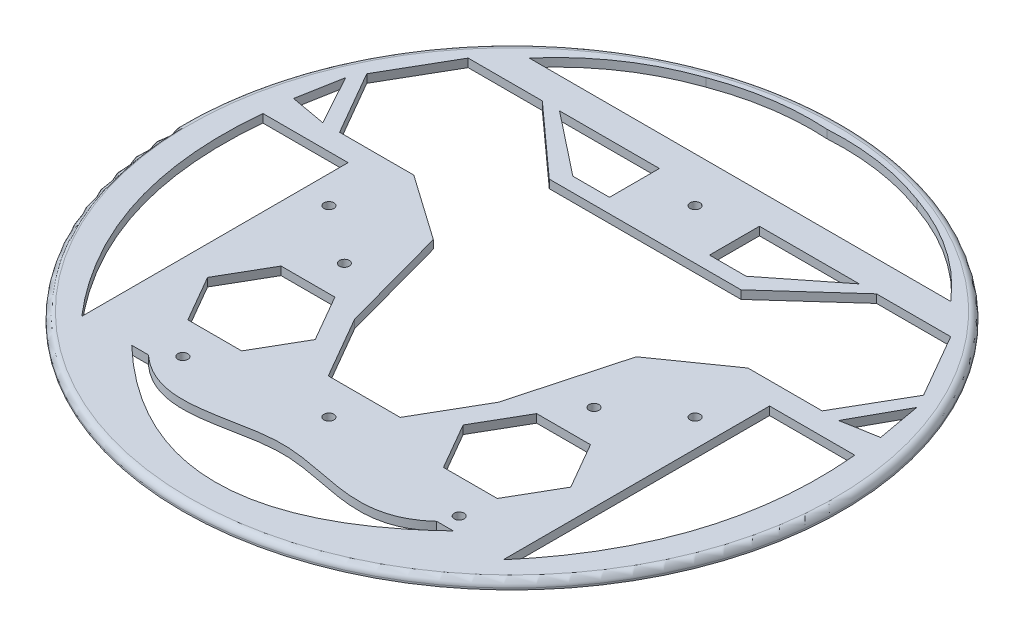
SolidWorks part; units mm, degrees
ref_plane "Front Plane" through (0, 0, 0) normal (0, 0, 1) x (1, 0, 0)
ref_plane "Top Plane" through (0, 0, 0) normal (0, 1, 0) x (1, 0, 0)
ref_plane "Right Plane" through (0, 0, 0) normal (1, 0, 0) x (0, 0, -1)
sketch "Sketch1" plane through (0, 0, 0) normal (0, 1, 0) x (1, 0, 0)
  circle A0 centre (0, 0) radius 99
extrude "Boss-Extrude1" add sketch "Sketch1" against normal blind 2.5 and the other way blind 4
sketch "Sketch3" plane through (0, 4, 0) normal (0, 1, 0) x (1, 0, 0)
  circle A0 centre (-55, 0) radius 1.5
  circle A1 centre (55, 0) radius 1.5
  circle A2 centre (0, -55) radius 1.5
extrude "Cut-Extrude2" cut sketch "Sketch3" against normal blind 20.5
sketch "Sketch4" plane through (0, 4, 0) normal (0, 1, 0) x (1, 0, 0)
  circle A0 centre (-37.676, -12.6871) radius 1.5
  circle A1 centre (-37.676, -61.1871) radius 1.5
  circle A2 centre (45.324, -61.1871) radius 1.5
  circle A3 centre (37.324, -12.6871) radius 1.5
extrude "Cut-Extrude3" cut sketch "Sketch4" against normal blind 20.5
sketch "Sketch5" plane through (0, 4, 0) normal (0, 1, 0) x (1, 0, 0)
  line L0 (0, 0) -> (0, 40)
  line L1 (28.8003, 40) -> (39.0457, 40)
  line L2 (28.8003, 40) -> (14.4001, 64.9418)
  line L3 (14.4001, 64.9418) -> (-14.4001, 64.9418)
  line L4 (-14.4001, 64.9418) -> (-28.8003, 40)
  line L5 (-28.8003, 40) -> (-14.4001, 15.0582)
  line L6 (-14.4001, 15.0582) -> (14.4001, 15.0582)
  line L7 (14.4001, 15.0582) -> (28.8003, 40)
  line L8 (21.6002, -25.6723) -> (10.8001, -6.966)
  line L9 (10.8001, -6.966) -> (-10.8001, -6.966)
  line L10 (-10.8001, -6.966) -> (-21.6002, -25.6723)
  line L11 (-21.6002, -25.6723) -> (-10.8001, -44.3786)
  line L12 (-10.8001, -44.3786) -> (10.8001, -44.3786)
  line L13 (10.8001, -44.3786) -> (21.6002, -25.6723)
  line L14 (83.6324, 40) -> (72.4857, 59.3066)
  line L15 (72.4857, 59.3066) -> (50.1924, 59.3066)
  line L16 (50.1924, 59.3066) -> (39.0457, 40)
  line L17 (39.0457, 40) -> (50.1924, 20.6934)
  line L18 (50.1924, 20.6934) -> (72.4857, 20.6934)
  line L19 (72.4857, 20.6934) -> (83.6324, 40)
  line L20 (-28.8003, 40) -> (-39.0503, 40)
  line L21 (0, 40) -> (-61.34, 40)
  line L24 (-39.0503, 40) -> (-50.1951, 59.3035)
  line L25 (-50.1951, 59.3035) -> (-72.4849, 59.3035)
  line L26 (-72.4849, 59.3035) -> (-83.6297, 40)
  line L27 (-83.6297, 40) -> (-72.4849, 20.6965)
  line L28 (-72.4849, 20.6965) -> (-50.1951, 20.6965)
  line L29 (-50.1951, 20.6965) -> (-39.0503, 40)
  circle A0 centre (0, 40) radius 24.9418 construction
  circle A1 centre (0, -25.6723) radius 18.7063 construction
  circle A2 centre (61.3391, 40) radius 19.3066 construction
  circle A3 centre (-61.34, 40) radius 19.3035 construction
extrude "Cut-Extrude4" cut sketch "Sketch5" against normal blind 10
sketch "Sketch6" plane through (0, 4, 0) normal (0, 1, 0) x (1, 0, 0)
  line L1 (-63.3094, 68.4789) -> (63.3094, 68.4789)
  line L2 (0, 68.4789) -> (0, 89.9578)
  line L3 (31.6547, 89.9578) -> (-31.6547, 89.9578)
  line L4 (0, 94.6904) -> (0, 89.9578)
  spline S0 degree 2 poles (-31.6547, 89.9578) (-50.3881, 83.4788) (-63.3094, 68.4789) knots 0 0 0 1 1 1
  spline S1 degree 2 poles (-31.6547, 89.9578) (-16.2344, 95.6989) (0, 94.6904) knots 0 0 0 1 1 1
  spline S2 degree 2 poles (31.6547, 89.9578) (16.2344, 95.6989) (0, 94.6904) knots 0 0 0 1 1 1
  spline S3 degree 2 poles (31.6547, 89.9578) (50.3881, 83.4788) (63.3094, 68.4789) knots 0 0 0 1 1 1
extrude "Cut-Extrude5" cut sketch "Sketch6" against normal blind 10 contours L3 S0 L1 L2 | S3 L3 L2 L1 | S1 L3 L4 | L3 S2 L4
sketch "Sketch7" plane through (0, 4, 0) normal (0, 1, 0) x (1, 0, 0)
  line L0 (-63.3094, -65.9369) -> (-63.3094, 14.0631)
  line L1 (-63.3094, -25.9369) -> (-75.4736, -25.9369)
  line L2 (-63.3094, 14.0631) -> (-88.8973, 14.0631)
  line L3 (-75.4736, -25.9369) -> (-85.4736, -25.9369)
  line L4 (0, 84.4217) -> (0, -91.9001)
  line L5 (63.3094, 14.0631) -> (88.8973, 14.0631)
  line L6 (63.3094, -65.9369) -> (63.3094, 14.0631)
  spline S0 degree 2 poles (-88.8973, 14.0631) (-93.2525, -31.1608) (-63.3094, -65.9369) knots 0 0 0 1 1 1
  spline S1 degree 2 poles (88.8973, 14.0631) (93.2525, -31.1608) (63.3094, -65.9369) knots 0 0 0 1 1 1
extrude "Cut-Extrude6" cut sketch "Sketch7" against normal blind 10 contours L2 S0 L3 L1 L0 | L3 S0 L0 L1 | S1 L5 L6
sketch "Sketch8" plane through (0, 4, 0) normal (0, 1, 0) x (1, 0, 0)
  line L1 (-63.3094, -65.9369) -> (-59.7739, -69.4724)
  line L2 (63.3094, -65.9369) -> (59.7739, -69.4724)
  line L4 (-121.0223, -77.0752) -> (-121.0223, -77.3515)
  line L5 (0, 0) -> (0, 55)
  line L6 (-14.4001, 64.9418) -> (14.4001, 64.9418)
  line L7 (14.4001, 64.9418) -> (28.8003, 40)
  line L8 (28.8003, 40) -> (-28.8003, 40)
  line L9 (-28.8003, 40) -> (-14.4001, 64.9418)
extrude "Boss-Extrude4" add sketch "Sketch8" against normal blind 6.5
sketch "Sketch9" plane through (0, 0, -14.0631) normal (0, 0, 1) x (1, 0, 0)
  line L6 (-99, -2.5) -> (-99, 1.5)
  line L7 (-99, 4) -> (-99, -2.5) construction
  line L8 (-99, 1.5) -> (99, 1.5)
  line L9 (99, -2.5) -> (99, 4) construction
  line L10 (99, 1.5) -> (99, -2.5)
  line L11 (99, -2.5) -> (-99, -2.5)
extrude "Cut-Extrude12" cut sketch "Sketch9" along normal blind 147.5 and the other way blind 90
sketch "Sketch15" plane through (0, 4, 0) normal (0, 1, 0) x (1, 0, 0)
  line L0 (0, 0) -> (0, 55)
  circle A0 centre (0, 55) radius 1.5
extrude "Cut-Extrude13" cut sketch "Sketch15" against normal blind 147.5
sketch "Sketch16" plane through (0, 4, 0) normal (0, 1, 0) x (1, 0, 0)
  line L0 (0, 0) -> (0, -0.0726)
  line L7 (0, -6.966) -> (-43.18, -6.966)
  line L8 (10.8001, -6.966) -> (-10.8001, -6.966) construction
  line L9 (-43.18, -6.966) -> (-43.18, 48.914)
  line L10 (0, -6.966) -> (43.18, -6.966)
  line L11 (43.18, -6.966) -> (43.18, 48.914)
  line L12 (43.18, 48.914) -> (-43.18, 48.914)
  line L13 (-50.1951, 59.3035) -> (-50.1951, 20.6965)
  line L14 (-50.1951, 20.6965) -> (-39.0503, 40)
  line L15 (-39.0503, 40) -> (-50.1951, 59.3035)
  line L16 (50.1924, 59.3066) -> (39.0457, 40)
  line L17 (39.0457, 40) -> (50.1924, 20.6934)
  line L18 (50.1924, 20.6934) -> (50.1924, 59.3066)
  line M18 (-50.1951, 59.3035) -> (-39.0503, 40)
  line M19 (-39.0503, 40) -> (-50.1951, 20.6965)
  line M21 (50.1924, 20.6934) -> (39.0457, 40)
  line M22 (39.0457, 40) -> (50.1924, 59.3066)
extrude "Boss-Extrude12" add sketch "Sketch16" against normal blind 2.5 contours L9 M19 M18 | L18 L11 M21 M22 | L11 M21 M22 | L13 L14 L15
sketch "Sketch17" plane through (0, 4, 0) normal (0, 1, 0) x (1, 0, 0)
  line L0 (0, -6.966) -> (-43.18, -6.966)
  line L1 (10.8001, -6.966) -> (-10.8001, -6.966) construction
  line L2 (-43.18, -6.966) -> (-43.18, 48.914)
  line L3 (0, -6.966) -> (43.18, -6.966)
  line L4 (43.18, -6.966) -> (43.18, 48.914)
  line L5 (43.18, 48.914) -> (-43.18, 48.914)
  line L6 (0, -22.8962) -> (0, -50.8962)
  line L7 (-22.2237, -36.8962) -> (-30.3066, -22.8962)
  line L8 (-30.3066, -22.8962) -> (-46.4724, -22.8962)
  line L9 (-46.4724, -22.8962) -> (-54.5553, -36.8962)
  line L10 (-54.5553, -36.8962) -> (-46.4724, -50.8962)
  line L11 (-46.4724, -50.8962) -> (-30.3066, -50.8962)
  line L12 (-30.3066, -50.8962) -> (-22.2237, -36.8962)
  line L13 (30.3066, -50.8962) -> (22.2237, -36.8962)
  line L14 (46.4724, -50.8962) -> (30.3066, -50.8962)
  line L15 (54.5553, -36.8962) -> (46.4724, -50.8962)
  line L16 (46.4724, -22.8962) -> (54.5553, -36.8962)
  line L17 (30.3066, -22.8962) -> (46.4724, -22.8962)
  line L18 (22.2237, -36.8962) -> (30.3066, -22.8962)
  circle A0 centre (-38.3895, -36.8962) radius 14 construction
extrude "Cut-Extrude14" cut sketch "Sketch17" against normal blind 2.5 contours L11 L12 L7 L8 L9 L10 | L18 L13 L14 L15 L16 L17
sketch "Sketch18" plane through (0, 4, 0) normal (0, 1, 0) x (1, 0, 0)
  line L0 (-63.3094, -65.9369) -> (-48.3094, -65.9369)
  line L1 (63.3094, -65.9369) -> (48.3094, -65.9369)
  line L2 (0, -99) -> (0, -89)
  line L3 (-48.3094, -65.9369) -> (-43.3094, -65.9369)
  line L4 (48.3094, -65.9369) -> (43.3094, -65.9369)
  line L5 (0, -89) -> (0, -69)
  line L6 (-28.4523, -81) -> (-23.5507, -72.2837)
  line L7 (28.4523, -81) -> (23.5507, -72.2837)
  circle A0 centre (0, 0) radius 99 construction
  spline S0 degree 2 poles (-48.3094, -65.9369) (0, -112.0631) (48.3094, -65.9369) knots 0 0 0 1 1 1
  spline S1 degree 3 poles (-43.3094, -65.9369) (-29.6148, -78.4073) (0, -59.5927) (29.6148, -78.4073) (43.3094, -65.9369) knots 0 0 0 0 0.5 1 1 1 1
extrude "Cut-Extrude15" cut sketch "Sketch18" against normal blind 2.5 contours S1 L6 S0 L5 | S1 L3 S0 L6 | S1 L5 S0 L7 | S1 L7 S0 L4
sketch "Sketch19" plane through (0, 4, 0) normal (0, 1, 0) x (1, 0, 0)
  line L14 (-10.8001, -6.966) -> (-30.3066, -22.8962)
  line L15 (-30.3066, -22.8962) -> (-14.4001, 15.0582)
  line L16 (-14.4001, 15.0582) -> (14.4001, 15.0582)
  line L17 (14.4001, 15.0582) -> (30.3066, -22.8962)
  line L18 (30.3066, -22.8962) -> (10.8001, -6.966)
  line L19 (10.8001, -6.966) -> (-10.8001, -6.966)
extrude "Boss-Extrude14" add sketch "Sketch19" against normal blind 2.5
sketch "Sketch20" plane through (0, 4, 0) normal (0, 1, 0) x (1, 0, 0)
  line L24 (-28.8003, 40) -> (-10.8001, -6.966)
  line L51 (-10.8001, -6.966) -> (10.8001, -6.966)
  line L52 (10.8001, -6.966) -> (28.8003, 40)
  line L53 (28.8003, 40) -> (14.4001, 15.0582)
  line L54 (14.4001, 15.0582) -> (-14.4001, 15.0582)
  line L55 (-14.4001, 15.0582) -> (-28.8003, 40)
extrude "Cut-Extrude28" cut sketch "Sketch20" against normal blind 2.5
sketch "Sketch24" plane through (0, 4, 0) normal (0, 1, 0) x (1, 0, 0)
  line L0 (28.8003, 40) -> (50.1924, 59.3066)
  line L1 (50.1924, 59.3066) -> (50.1924, 20.6934)
  line L2 (50.1924, 20.6934) -> (10.8001, -6.966)
  line L3 (10.8001, -6.966) -> (28.8003, 40)
  line L4 (0, 71.9114) -> (0, -11.4942)
  line L9 (-50.1951, 59.3035) -> (-28.8003, 40)
  line L10 (-28.8003, 40) -> (-10.8001, -6.966)
  line L11 (-10.8001, -6.966) -> (-50.1951, 20.6965)
  line L12 (-50.1951, 20.6965) -> (-50.1951, 59.3035)
extrude "Cut-Extrude30" cut sketch "Sketch24" against normal blind 2.5 contours L12 L11 L10 L9 | L3 L2 L1 L0
sketch "Sketch25" plane through (0, 4, 0) normal (0, 1, 0) x (1, 0, 0)
  line L0 (-45.0274, 59.3035) -> (-15.0274, 59.3035)
  line L1 (-15.0274, 59.3035) -> (-15.0274, 44.3035)
  line L2 (-15.0274, 44.3035) -> (-26.0274, 44.3035)
  line L3 (-26.0274, 44.3035) -> (-45.0274, 59.3035)
  line L4 (0, 67.1439) -> (0, 47.2304)
  line L5 (15.0274, 44.3035) -> (26.0274, 44.3035)
  line L6 (15.0274, 59.3035) -> (15.0274, 44.3035)
  line L7 (45.0274, 59.3035) -> (15.0274, 59.3035)
  line L8 (26.0274, 44.3035) -> (45.0274, 59.3035)
extrude "Cut-Extrude31" cut sketch "Sketch25" against normal blind 2.5 contours L3 L2 L1 L0 | L5 L8 L7 L6
sketch "Sketch26" plane through (0, 4, 0) normal (0, 1, 0) x (1, 0, 0)
  line L0 (-21.6002, -25.6723) -> (-30.4976, 6.8653)
  line L1 (-10.8001, -6.966) -> (-50.1951, 20.6965) construction
  line L2 (21.6002, -25.6723) -> (30.4963, 6.8637)
  line L3 (50.1924, 20.6934) -> (10.8001, -6.966) construction
  line L4 (30.4963, 6.8637) -> (-30.4976, 6.8653)
  line L5 (-21.6002, -25.6723) -> (21.6002, -25.6723)
extrude "Cut-Extrude32" cut sketch "Sketch26" against normal blind 2.5
sketch "Sketch27" plane through (0, 4, 0) normal (0, 1, 0) x (1, 0, 0)
  line L0 (-88.1735, 22.569) -> (-85.7911, 35.8045)
  line L1 (-85.7911, 35.8045) -> (-77.4559, 20.6399)
  line L2 (-77.4559, 20.6399) -> (-88.1735, 22.569)
  line L3 (0, 47.4517) -> (0, -10.5195)
  line L4 (85.7911, 35.8045) -> (77.4559, 20.6399)
  line L5 (88.1735, 22.569) -> (85.7911, 35.8045)
  line L6 (77.4559, 20.6399) -> (88.1735, 22.569)
extrude "Cut-Extrude33" cut sketch "Sketch27" against normal blind 2.5 contours L0 L1 L2 | L5 L4 L6
fillet "Fillet1" radius 2 1 edges at (0, 4, 99)
